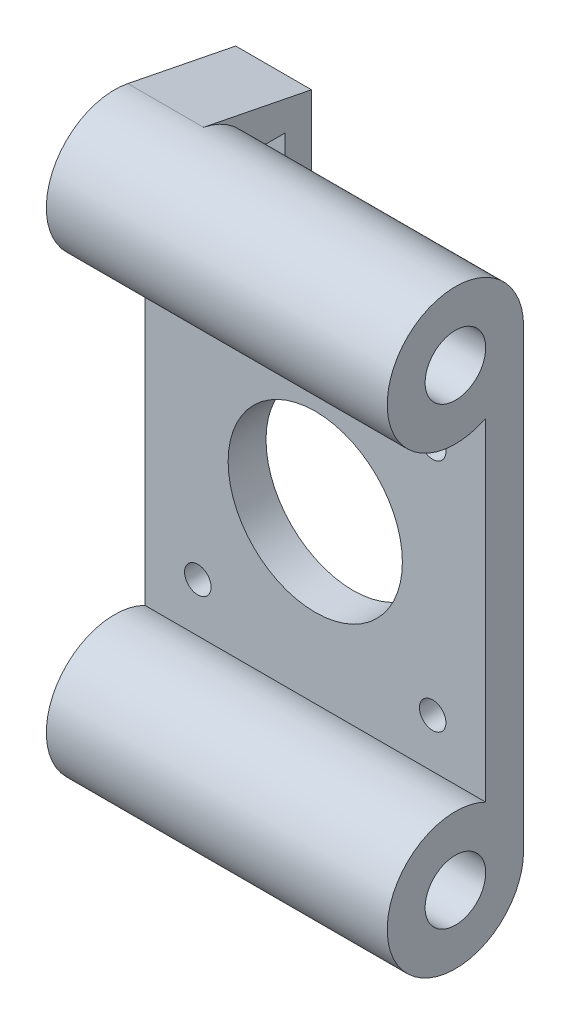
SolidWorks part; units mm, degrees
material "ABS"
ref_plane "Plano frontal" through (0, 0, 0) normal (0, 0, 1) x (1, 0, 0)
ref_plane "Plano superior" through (0, 0, 0) normal (0, 1, 0) x (1, 0, 0)
ref_plane "Plano direito" through (0, 0, 0) normal (1, 0, 0) x (0, 0, -1)
sketch "Esboço1" plane through (0, 0, 0) normal (0, 0, 1) x (1, 0, 0)
  line L1 (-22.5, 22.5) -> (22.5, 22.5)
  line L2 (-22.5, 22.5) -> (-22.5, -22.5)
  line L3 (-22.5, -22.5) -> (22.5, -22.5)
  line L4 (22.5, 22.5) -> (22.5, -22.5)
  line L5 (-22.5, 22.5) -> (22.5, -22.5) construction
  line L6 (-22.5, -22.5) -> (22.5, 22.5) construction
  circle A0 centre (-15.5, 15.5) radius 1.75
  circle A1 centre (15.5, 15.5) radius 1.75
  circle A2 centre (15.5, -15.5) radius 1.75
  circle A3 centre (-15.5, -15.5) radius 1.75
  circle A4 centre (0, 0) radius 11.5
  point P0 (0, 0)
  point P17 (0, 0)
  dimension "D2" = 3.5
  dimension "D4" = 31
  dimension "D5" = 23
  dimension "D1" = 45
  dimension "D3" = 4
extrude "Ressalto-extrusão1" add sketch "Esboço1" along normal blind 5
sketch "Esboço3" plane through (-22.5, 0, 0) normal (-1, 0, 0) x (0, 0, 1)
  line L0 (0, 30) -> (0, 21.9377)
  line L1 (0, 22.5) -> (0, -22.5) construction
  line L3 (0, 0) -> (21.5803, 0) construction
  line L5 (5, 21.9377) -> (0, 21.9377)
  line L6 (5, -21.9377) -> (0, -21.9377)
  line L7 (0, -21.9377) -> (0, -30)
  circle A0 centre (9, 30) radius 4
  arc A1 (5, 21.9377) -> (0, 30) centre (9, 30) ccw
  arc A2 (5, -21.9377) -> (0, -30) centre (9, -30) cw
  circle A3 centre (9, -30) radius 4
  point P14 (5, 0)
  dimension "D1" = 18
  dimension "D2" = 8
  dimension "D3" = 30
extrude "Ressalto-extrusão2" add sketch "Esboço3" against normal up to surface (45 mm away) up to face at (22.5, 0, 2.5)
sketch "Esboço4" plane through (-22.5, 0, 0) normal (-1, 0, 0) x (0, 0, 1)
  line L0 (-7, 30) -> (5, 30) construction
  line L1 (7.2479, 38.8278) -> (-7, 36)
  line L2 (-7, 36) -> (-7, 24)
  line L3 (-7, 24) -> (0, 22.6107)
  line L4 (0, 30) -> (0, -30) construction
  line L5 (0, 30) -> (0, 32.8)
  line L6 (0, 32.8) -> (-3.5, 32.8)
  line L7 (-3.5, 32.8) -> (-3.5, 27.2)
  line L8 (-3.5, 27.2) -> (0, 27.2)
  line L9 (0, 27.2) -> (0, 30)
  line L10 (7.2479, 38.8278) -> (0, 22.6107)
  line L11 (-6.3391, 0) -> (17.1601, 0) construction
  line L12 (-7, -30) -> (5, -30) construction
  line L13 (7.2479, -38.8278) -> (0, -22.6107)
  line L14 (0, -27.2) -> (0, -30)
  line L15 (-3.5, -27.2) -> (0, -27.2)
  line L16 (-3.5, -32.8) -> (-3.5, -27.2)
  line L17 (0, -32.8) -> (-3.5, -32.8)
  line L18 (0, -30) -> (0, -32.8)
  line L19 (-7, -24) -> (0, -22.6107)
  line L20 (-7, -36) -> (-7, -24)
  line L21 (7.2479, -38.8278) -> (-7, -36)
  arc A1 (5, 21.9377) -> (0, 30) centre (9, 30) ccw construction
  point P0 (-7, 30)
  point P3 (5, 30)
  point P18 (-3.5, 30)
  dimension "D1" = 7
  dimension "D2" = 12
  dimension "D3" = 3.5
  dimension "D4" = 5.6
extrude "Ressalto-extrusão3" add sketch "Esboço4" against normal blind 10
sketch "Esboço5" plane through (0, 0, -7) normal (0, 0, -1) x (-1, 0, 0)
  line L0 (12.5, 36) -> (22.5, 24) construction
  line L1 (0, 0) -> (33.7269, 0) construction
  circle A0 centre (17.5, 30) radius 1.75
  circle A1 centre (17.5, -30) radius 1.75
  dimension "D1" = 3.5
extrude "Corte-extrusão2" cut sketch "Esboço5" against normal blind 15
